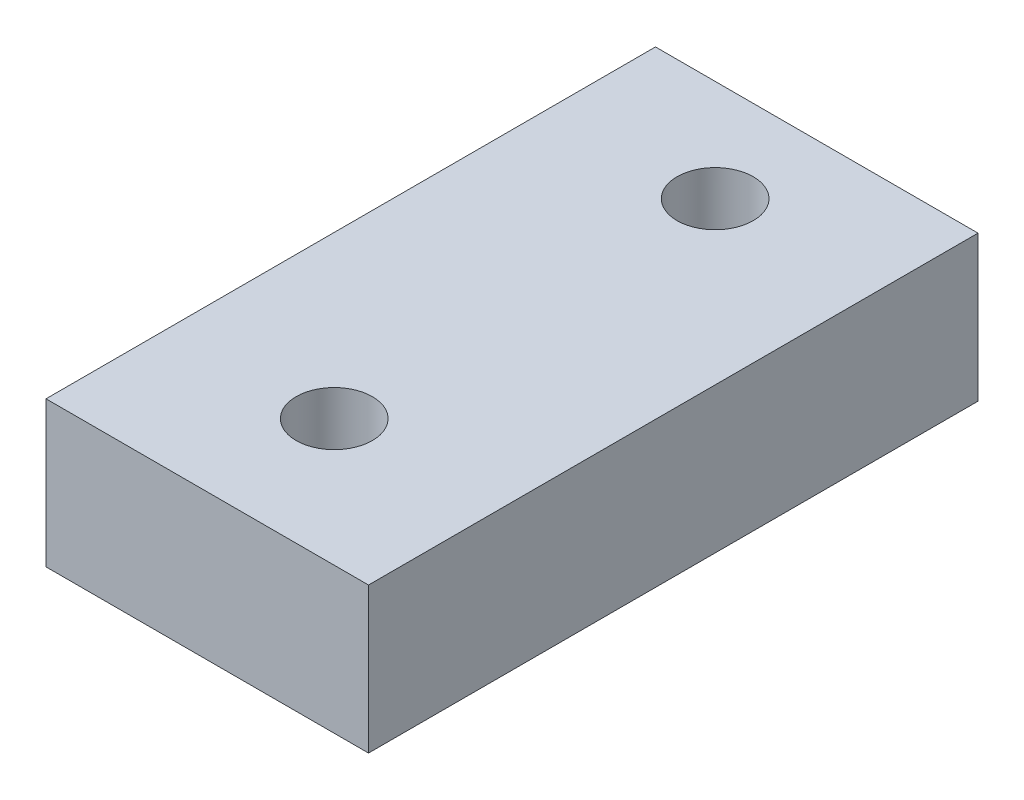
SolidWorks part; units mm, degrees
ref_plane "Front Plane" through (0, 0, 0) normal (0, 0, 1) x (1, 0, 0)
ref_plane "Top Plane" through (0, 0, 0) normal (0, 1, 0) x (1, 0, 0)
ref_plane "Right Plane" through (0, 0, 0) normal (1, 0, 0) x (0, 0, -1)
ref_plane "Plane1" through (0, -66.9079, 0) normal (0, -1, 0) x (-1, 0, 0)
sketch "Sketch1" plane through (0, -66.9079, 0) normal (0, -1, 0) x (-1, 0, 0)
  line L0 (-49.5841, -30.2538) -> (-49.5841, -110.2538) construction
  line L1 (-62.2841, -110.2538) -> (-49.5841, -110.2538)
  line L2 (-62.2841, -110.2538) -> (-62.2841, -86.2538)
  line L3 (-62.2841, -86.2538) -> (-49.5841, -86.2538)
  line L4 (-49.5841, -110.2538) -> (-49.5841, -86.2538)
  circle A0 centre (-55.9341, -90.2538) radius 1.5
  circle A1 centre (-55.9341, -105.2538) radius 1.5
  dimension "D1" = 24
extrude "Boss-Extrude1" add sketch "Sketch1" against normal up to body (5.7318 mm away) separate body
